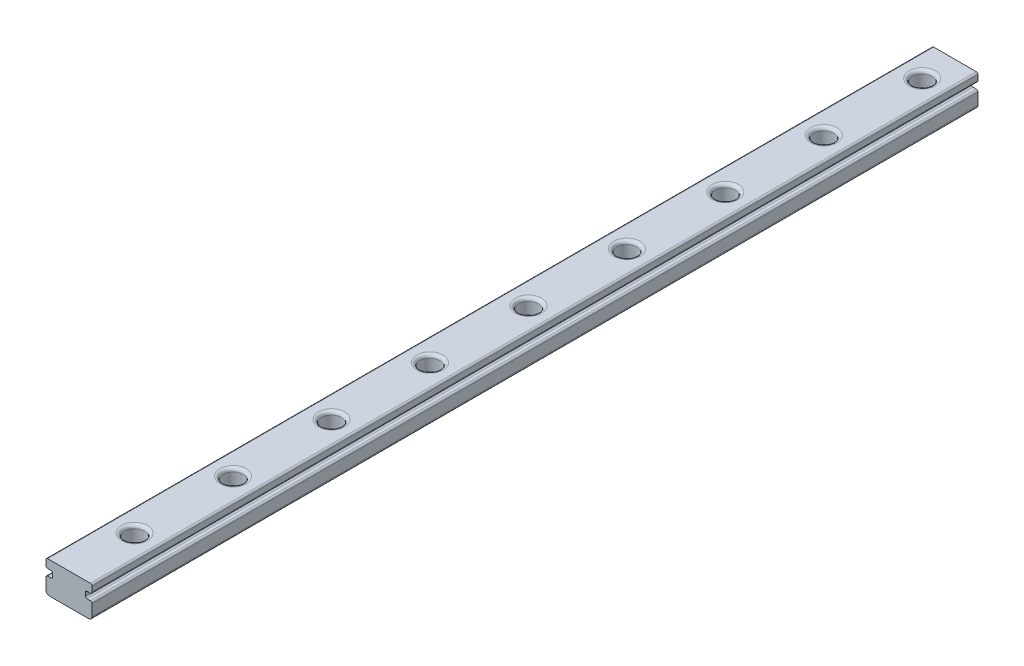
SolidWorks part; units mm, degrees
material "201 退火不锈钢 (SS)"
ref_plane "前视基准面" through (0, 0, 0) normal (0, 0, 1) x (1, 0, 0)
ref_plane "上视基准面" through (0, 0, 0) normal (0, 1, 0) x (1, 0, 0)
ref_plane "右视基准面" through (0, 0, 0) normal (1, 0, 0) x (0, 0, -1)
sketch "草图1" plane through (0, 0, 0) normal (0, 0, 1) x (1, 0, 0)
  line L0 (0, 0) -> (7, 0)
  line L1 (0, 3.5) -> (0, 4.8)
  line L2 (0, 4.8) -> (7, 4.8)
  line L3 (7, 4.8) -> (7, 3.5)
  line L4 (0, 4.8) -> (0, 3.5)
  line L5 (0, 2.5) -> (1, 2.5)
  line L6 (1, 2.5) -> (1, 3.5)
  line L7 (1, 3.5) -> (0, 3.5)
  line L8 (7, 3.5) -> (6, 3.5)
  line L9 (6, 3.5) -> (6, 2.5)
  line L10 (6, 2.5) -> (7, 2.5)
  line L11 (0, 2.5) -> (0, 0)
  line L12 (7, 2.5) -> (7, 0)
extrude "凸台-拉伸1" add sketch "草图1" along normal blind 135 contours L12 L10 L9 L8 L3 L2 L1 L7 L6 L5 L11 L0
fillet "圆角1" radius 0.25 10 edges at (7, 2.5, 67.5) (0, 2.5, 67.5) (1, 3.5, 67.5) (1, 2.5, 67.5) (6, 2.5, 67.5) (6, 3.5, 67.5) (7, 4.8, 67.5) (0, 4.8, 67.5) (0, 3.5, 67.5) (7, 3.5, 67.5)
fillet "圆角2" radius 0.5 2 edges at (0, 0, 67.5) (7, 0, 67.5)
sketch "草图2" plane through (0, 4.8, 0) normal (0, 1, 0) x (1, 0, 0)
  line L0 (0.25, 0) -> (6.75, 0) construction
  line L1 (3.5, 0) -> (3.5, -6.7471) construction
  circle A0 centre (3.5, -5) radius 1.5
  dimension "D1" = 3
  dimension "D2" = 5
extrude "切除-拉伸1" cut sketch "草图2" against normal blind 2.3
sketch "草图3" plane through (0, 2.5, 0) normal (0, 1, 0) x (1, 0, 0)
  line L0 (0.5, 0) -> (6.5, 0) construction
  line L1 (3.5, 0) -> (3.5, -4.4975) construction
  circle A0 centre (3.5, -5) radius 1.5 construction
  circle A1 centre (3.5, -5) radius 1.2
  dimension "D1" = 2.4
extrude "切除-拉伸2" cut sketch "草图3" against normal through all
fillet "圆角3" radius 0.5 1 edges at (3.5, 4.8, 6.5)
pattern_linear "阵列(线性)2" count 9 spacing 15 along (0, 0, 1) of "切除-拉伸1", "切除-拉伸2", "圆角3"
